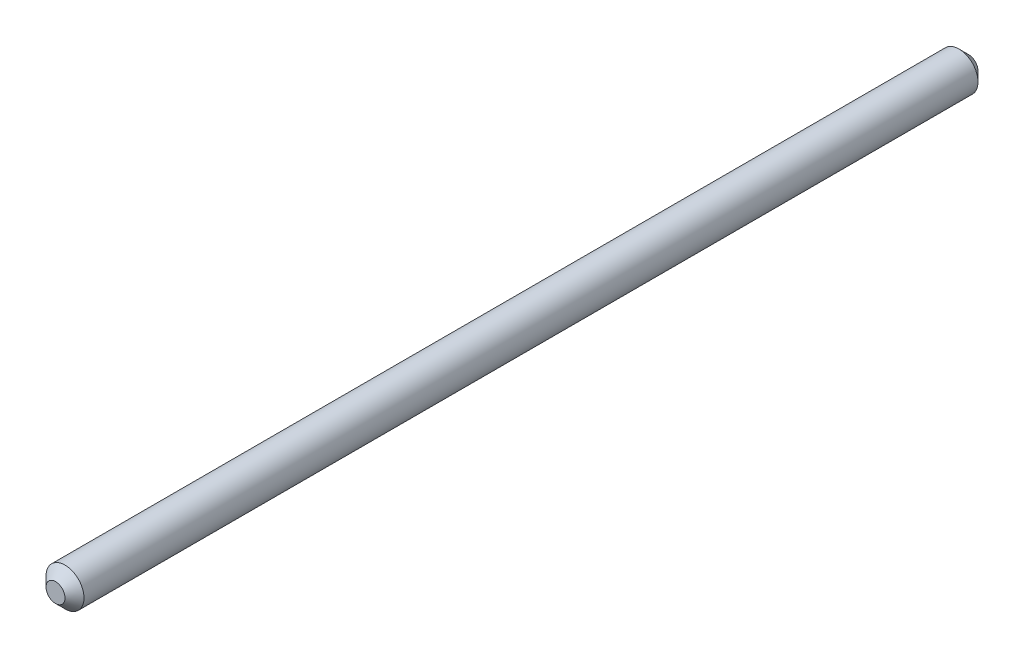
SolidWorks part; units mm, degrees
ref_plane "Front Plane" through (0, 0, 0) normal (0, 0, 1) x (1, 0, 0)
ref_plane "Top Plane" through (0, 0, 0) normal (0, 1, 0) x (1, 0, 0)
ref_plane "Right Plane" through (0, 0, 0) normal (1, 0, 0) x (0, 0, -1)
sketch "Sketch1" plane through (0, 0, 0) normal (0, 0, 1) x (1, 0, 0)
  circle A0 centre (0, 0) radius 1
  dimension "D1" = 2
extrude "Boss-Extrude1" add sketch "Sketch1" against normal blind 48
chamfer "Chamfer1" distance 0.5 angle 45 2 edges at (1, 0, -48) (1, 0, 0)
